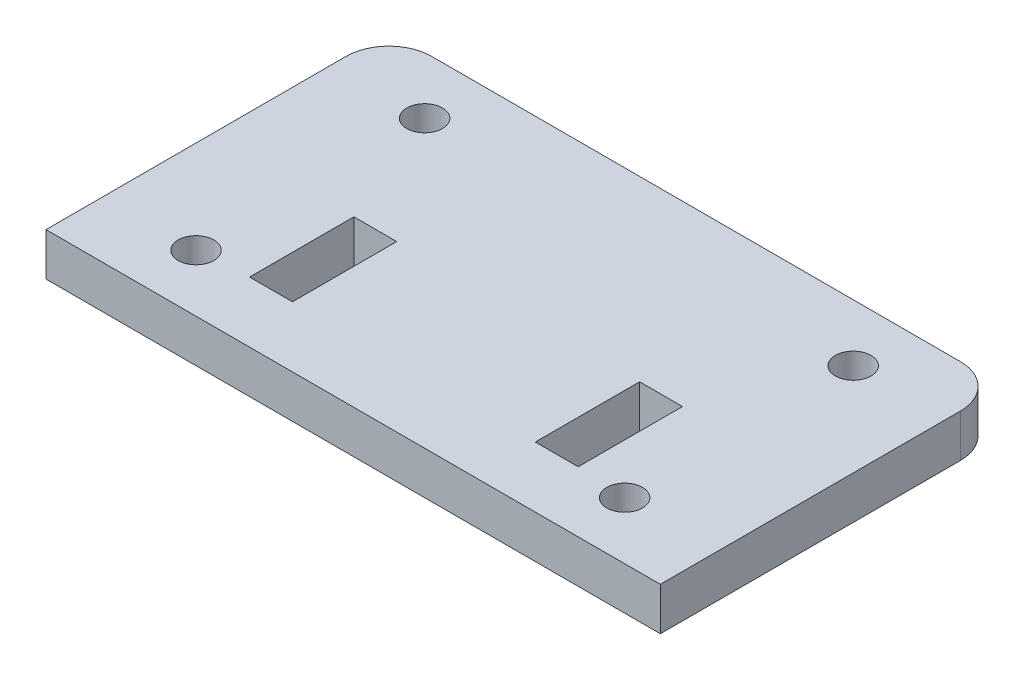
SolidWorks part; units mm, degrees
ref_plane "Plan de face" through (0, 0, 0) normal (0, 0, 1) x (1, 0, 0)
ref_plane "Plan de dessus" through (0, 0, 0) normal (0, 1, 0) x (1, 0, 0)
ref_plane "Plan de droite" through (0, 0, 0) normal (1, 0, 0) x (0, 0, -1)
sketch "Esquisse1" plane through (0, 0, 0) normal (0, 1, 0) x (1, 0, 0)
  line L0 (0, 0) -> (0, 24) construction
  line L1 (-18.5, 24) -> (18.5, 24)
  line L2 (-21.5, 21) -> (-21.5, 0)
  line L3 (-21.5, 0) -> (21.5, 0)
  line L4 (21.5, 21) -> (21.5, 0)
  line L5 (-11.5, 11.55) -> (-8.5, 11.55)
  line L6 (-11.5, 11.55) -> (-11.5, 4.25)
  line L7 (-11.5, 4.25) -> (-8.5, 4.25)
  line L8 (-8.5, 11.55) -> (-8.5, 4.25)
  line L9 (11.5, 4.25) -> (8.5, 4.25)
  line L10 (8.5, 11.55) -> (8.5, 4.25)
  line L11 (11.5, 11.55) -> (8.5, 11.55)
  line L12 (11.5, 11.55) -> (11.5, 4.25)
  line L14 (-15, 20) -> (15, 20) construction
  line L15 (-15, 20) -> (-15, 4) construction
  line L16 (-15, 4) -> (15, 4) construction
  line L17 (15, 20) -> (15, 4) construction
  circle A0 centre (-15, 20) radius 1.25
  circle A1 centre (15, 20) radius 1.25
  circle A2 centre (15, 4) radius 1.25
  circle A3 centre (-15, 4) radius 1.25
  arc A4 (18.5, 24) -> (21.5, 21) centre (18.5, 21) cw
  arc A5 (-18.5, 24) -> (-21.5, 21) centre (-18.5, 21) ccw
  point P4 (0, 0)
  point P24 (0, 20)
  point P27 (21.5, 24)
  point P30 (-21.5, 24)
  dimension "D7" = 2.5
  dimension "D11" = 3
  dimension "D1" = 43
  dimension "D2" = 24
  dimension "D3" = 7.3
  dimension "D4" = 3
  dimension "D5" = 4.25
  dimension "D6" = 8.5
  dimension "D8" = 16
  dimension "D9" = 30
  dimension "D10" = 4
extrude "Boss.-Extru.1" add sketch "Esquisse1" along normal blind 3
